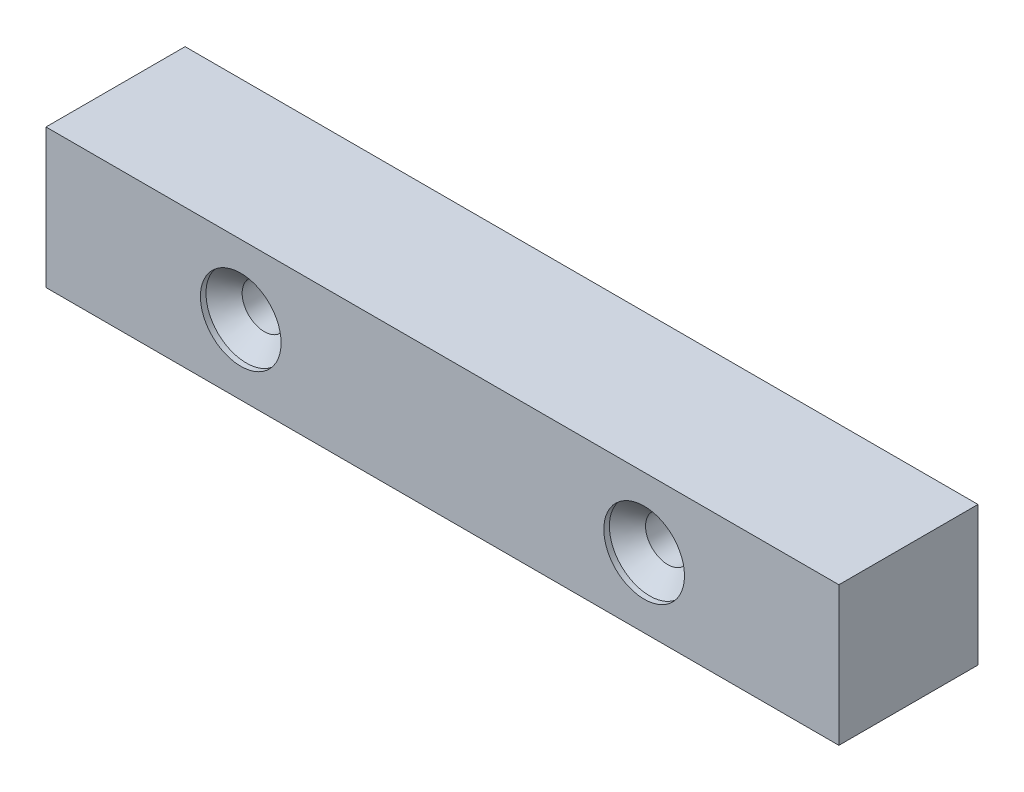
SolidWorks part; units mm, degrees
ref_plane "Plan de face" through (0, 0, 0) normal (0, 0, 1) x (1, 0, 0)
ref_plane "Plan de dessus" through (0, 0, 0) normal (0, 1, 0) x (1, 0, 0)
ref_plane "Plan de droite" through (0, 0, 0) normal (1, 0, 0) x (0, 0, -1)
sketch "Esquisse1" plane through (0, 0, 0) normal (0, 0, 1) x (1, 0, 0)
  line L1 (-28.5, -17.2195) -> (28.5, -17.2195)
  line L2 (-28.5, -17.2195) -> (-28.5, -27.2195)
  line L3 (-28.5, -27.2195) -> (28.5, -27.2195)
  line L4 (28.5, -17.2195) -> (28.5, -27.2195)
extrude "Boss.-Extru.1" add sketch "Esquisse1" along normal blind 10
hole_wizard "Fraisage pour vis à tête fraisée à 6 pans creux M31" positions "Esquisse7" profile "Esquisse6" countersink size "M3" standard "ISO" end condition up to next
sketch "Esquisse7" plane through (0, 0, 10) normal (0, 0, 1) x (1, 0, 0)
  point P0 (-14.5, -22.2195)
  point P4 (14.5, -22.2195)
sketch "Esquisse6" plane through (-14.5, -22.2195, 10) normal (1, 0, 0) x (0, -1, 0)
  line L0 (0, 0) -> (0, 10)
  line L1 (0, 10) -> (1.6, 10)
  line L2 (1.6, 10) -> (1.6, 1.7)
  line L3 (1.6, 1.7) -> (2.9, 0.4)
  line L4 (2.9, 0.4) -> (2.9, 0)
  line L6 (2.9, 0) -> (0, 0)
  line L7 (-1.6, 1.7) -> (-2.9, 0.4) construction
  line L11 (0, -6.35) -> (0, 107.95) construction
  dimension "Diamètre du perçage jusqu'au prochain" = 3.2
  dimension "Profondeur du perçage jusqu'au prochain" = 10
  dimension "Diamètre du fraisage" = 5.8
  dimension "Angle du fraisage" = 90
  dimension "Dégagement de la tête" = 0.4
sketch "Esquisse8" plane through (0, 0, 0) normal (0, 0, -1) x (-1, 0, 0)
  circle A0 centre (-23.5, -22.2195) radius 1.55
  circle A1 centre (-23.5, -22.2195) radius 1.55 construction
extrude "Enlèv. mat.-Extru.1" cut sketch "Esquisse8" against normal blind 5
mirror "Symétrie1" about plane through (0, 0, 0) normal (1, 0, 0) of "Enlèv. mat.-Extru.1"
